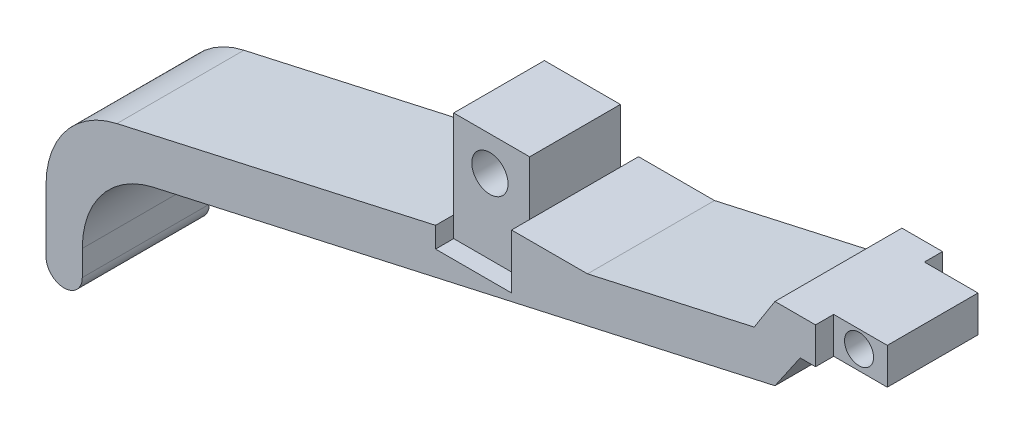
SolidWorks part; units mm, degrees
ref_plane "Front Plane" through (0, 0, 0) normal (0, 0, 1) x (1, 0, 0)
ref_plane "Top Plane" through (0, 0, 0) normal (0, 1, 0) x (1, 0, 0)
ref_plane "Right Plane" through (0, 0, 0) normal (1, 0, 0) x (0, 0, -1)
sketch "Sketch1" plane through (0, 0, 0) normal (0, 0, 1) x (1, 0, 0)
  line L5 (3.1534, 12.2471) -> (4.2965, 14.0434)
  line L7 (4.2965, 10.0175) -> (5.6873, 12.0434)
  line L11 (-31.9745, 4.3996) -> (3.1534, 12.2471)
  line L12 (4.2965, 10.0175) -> (-29.9745, 2.3615)
  line L13 (-33.8844, -2.5182) -> (-33.8844, -3.9095)
  line L14 (-35.8844, -3.9095) -> (-35.8844, -0.4801)
  line L15 (4.2965, 14.0434) -> (9.4894, 14.0434)
  line L16 (9.4894, 14.0434) -> (9.4894, 12.0434)
  line L17 (9.4894, 12.0434) -> (5.6873, 12.0434)
  arc A0 (-33.8844, -3.9095) -> (-35.8844, -3.9095) centre (-34.8844, -3.9095) cw
  arc A1 (-29.9745, 2.3615) -> (-33.8844, -2.5182) centre (-28.8844, -2.5182) ccw
  arc A2 (-35.8844, -0.4801) -> (-31.9745, 4.3996) centre (-30.8844, -0.4801) cw
  point P15 (-35.7843, 3.0898)
  dimension "D4" = 2
  dimension "D5" = 5
  dimension "D6" = 5
  dimension "D2" = 40
  dimension "D3" = 7
  dimension "D1" = 2
extrude "Boss-Extrude2" add sketch "Sketch1" along normal blind 7
sketch "Sketch2" plane through (0, 0, 7) normal (0, 0, 1) x (1, 0, 0)
  line L0 (-6.0348, 10.1945) -> (-10.2227, 10.1945)
  line L1 (3.1534, 12.2471) -> (-31.9745, 4.3996) construction
  line L2 (-14.4105, 10.1945) -> (-14.4105, 8.3234)
  line L3 (-14.4105, 8.3234) -> (-6.0348, 10.1945)
  line L4 (-10.2227, 10.1945) -> (-10.2227, 13.1883)
  line L5 (-10.2227, 13.1883) -> (-14.4105, 13.1883)
  line L6 (-14.4105, 13.1883) -> (-14.4105, 10.1945)
extrude "Boss-Extrude3" add sketch "Sketch2" against normal blind 7
sketch "Sketch3" plane through (0, 0, 7) normal (0, 0, 1) x (1, 0, 0)
  circle A0 centre (-12.4148, 11.2999) radius 1
extrude "Cut-Extrude1" cut sketch "Sketch3" against normal blind 7
sketch "Sketch4" plane through (0, 0, 7) normal (0, 0, 1) x (1, 0, 0)
  circle A0 centre (7.9323, 13.0902) radius 0.8
extrude "Cut-Extrude2" cut sketch "Sketch4" against normal blind 7
sketch "Sketch6" plane through (0, 12.0434, 0) normal (0, -1, 0) x (1, 0, 0)
  line L0 (6.5344, 7) -> (6.5344, 6)
  line L1 (5.6873, 7) -> (9.4894, 7) construction
  line L2 (6.5344, 6) -> (9.4894, 6)
  line L3 (9.4894, 7) -> (9.4894, 0) construction
  line L4 (6.5344, 0) -> (6.5344, 1)
  line L5 (5.6873, 0) -> (9.4894, 0) construction
  line L6 (6.5344, 1) -> (9.4894, 1)
  line L7 (9.4894, 6) -> (9.4894, 7)
  line L8 (9.4894, 7) -> (6.5344, 7)
  line L9 (9.4894, 1) -> (9.4894, 0)
  line L10 (9.4894, 0) -> (6.5344, 0)
  dimension "D1" = 1
  dimension "D2" = 2.955
  dimension "D3" = 1
extrude "Cut-Extrude3" cut sketch "Sketch6" against normal blind 10
sketch "Sketch7" plane through (0, 13.1883, 0) normal (0, 1, 0) x (1, 0, 0)
  line L1 (-14.4105, 0) -> (-14.4105, -1)
  line L2 (-14.4105, 0) -> (-14.4105, -7) construction
  line L3 (-14.4105, -1) -> (-10.2227, -1)
  line L4 (-10.2227, 0) -> (-10.2227, -7) construction
  line L5 (-10.2227, -1) -> (-10.2227, 0)
  line L6 (-10.2227, 0) -> (-14.4105, 0)
  line L7 (-14.4105, -7) -> (-14.4105, -6)
  line L8 (-14.4105, -6) -> (-10.2227, -6)
  line L9 (-10.2227, -6) -> (-10.2227, -7)
  line L10 (-10.2227, -7) -> (-14.4105, -7) construction
  line L11 (-10.2227, -7) -> (-14.4105, -7)
  dimension "D1" = 1
  dimension "D2" = 1
extrude "Cut-Extrude5" cut sketch "Sketch7" against normal blind 6
